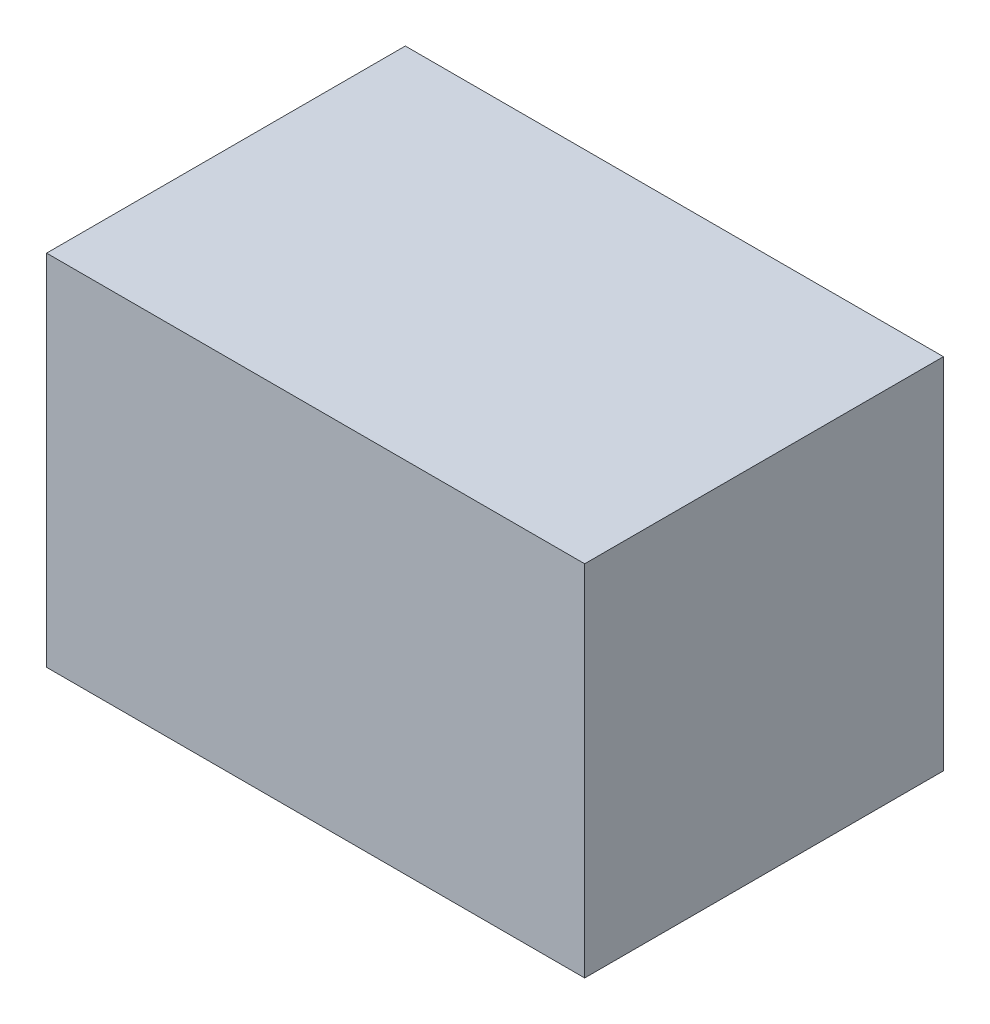
SolidWorks part; units mm, degrees
ref_plane "Front Plane" through (0, 0, 0) normal (0, 0, 1) x (1, 0, 0)
ref_plane "Top Plane" through (0, 0, 0) normal (0, 1, 0) x (1, 0, 0)
ref_plane "Right Plane" through (0, 0, 0) normal (1, 0, 0) x (0, 0, -1)
other "Configuration Table"
sketch "Sketch1" plane through (0, 0, 0) normal (0, 0, 1) x (1, 0, 0)
  line L1 (550, 900) -> (580, 900)
  line L2 (550, 900) -> (550, 920)
  line L3 (550, 920) -> (580, 920)
  line L4 (580, 900) -> (580, 920)
extrude "PACK_kapak_switch_2_1" add sketch "Sketch1" against normal blind 20 from offset 620 separate body
